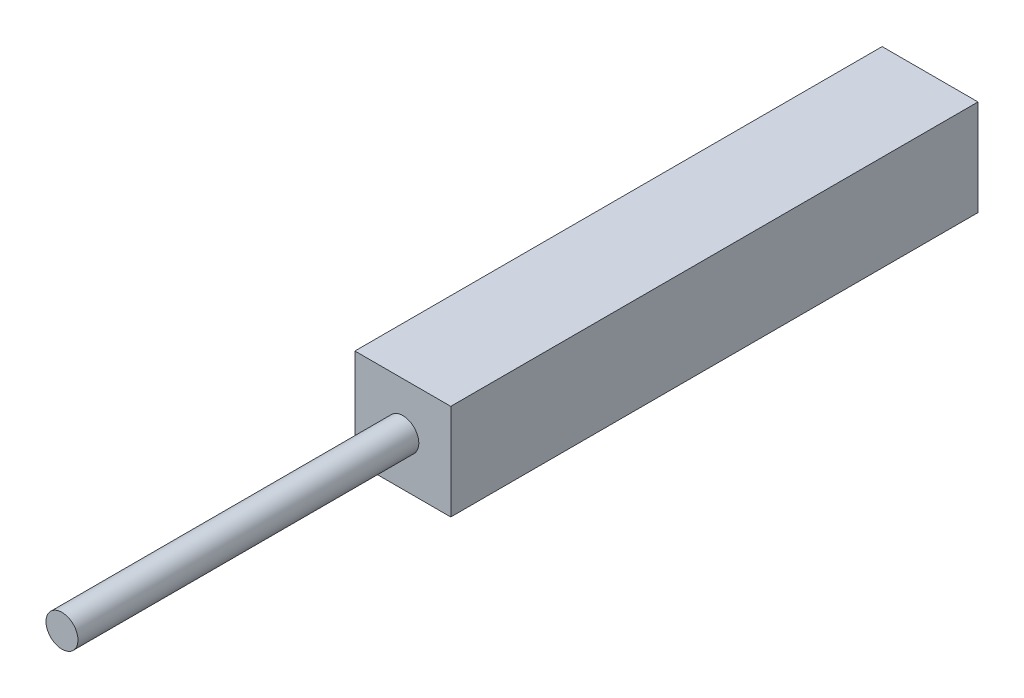
SolidWorks part; units mm, degrees
ref_plane "前视基准面" through (0, 0, 0) normal (0, 0, 1) x (1, 0, 0)
ref_plane "上视基准面" through (0, 0, 0) normal (0, 1, 0) x (1, 0, 0)
ref_plane "右视基准面" through (0, 0, 0) normal (1, 0, 0) x (0, 0, -1)
sketch "草图1" plane through (0, 0, 0) normal (0, 0, 1) x (1, 0, 0)
  line L1 (-9, -9) -> (9, -9)
  line L2 (-9, -9) -> (-9, 9)
  line L3 (-9, 9) -> (9, 9)
  line L4 (9, -9) -> (9, 9)
  line L5 (-9, -9) -> (9, 9) construction
  line L6 (-9, 9) -> (9, -9) construction
  point P0 (0, 0)
  dimension "D1" = 18
extrude "凸台-拉伸1" add sketch "草图1" along normal blind 99
sketch "草图2" plane through (0, 0, 99) normal (0, 0, 1) x (1, 0, 0)
  circle A0 centre (0, 0) radius 3
  dimension "D1" = 6
extrude "凸台-拉伸2" add sketch "草图2" along normal blind 64
